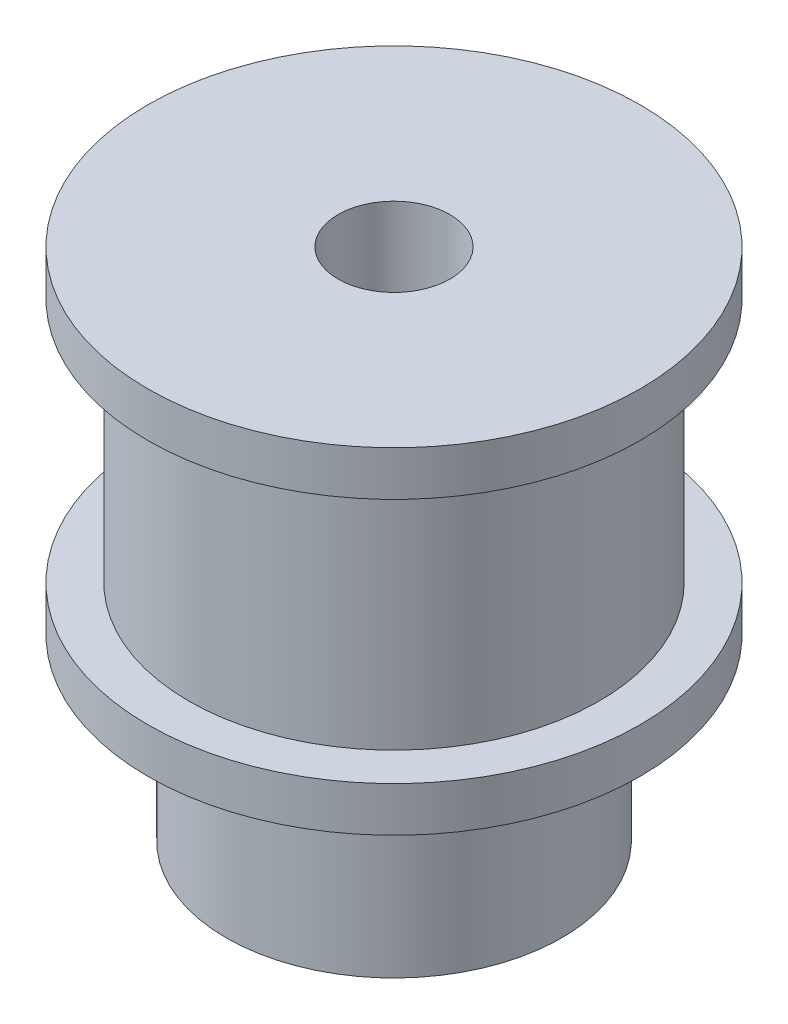
SolidWorks part; units mm, degrees
material "AISI 304"
ref_plane "前视基准面" through (0, 0, 0) normal (0, 0, 1) x (1, 0, 0)
ref_plane "上视基准面" through (0, 0, 0) normal (0, 1, 0) x (1, 0, 0)
ref_plane "右视基准面" through (0, 0, 0) normal (1, 0, 0) x (0, 0, -1)
other "Configuration Table"
sketch "草图1" plane through (0, 0, 0) normal (0, 1, 0) x (1, 0, 0)
  circle A0 centre (0, 0) radius 11
  dimension "D1" = 22
extrude "凸台-拉伸1" add sketch "草图1" along normal blind 2
sketch "草图2" plane through (0, 2, 0) normal (0, 1, 0) x (1, 0, 0)
  circle A0 centre (0, 0) radius 9.17
  dimension "D1" = 18.34
extrude "凸台-拉伸2" add sketch "草图2" along normal blind 11
sketch "草图3" plane through (0, 13, 0) normal (0, 1, 0) x (1, 0, 0)
  circle A0 centre (0, 0) radius 11
  dimension "D1" = 22
extrude "凸台-拉伸3" add sketch "草图3" along normal blind 2
sketch "草图4" plane through (0, 15, 0) normal (0, 1, 0) x (1, 0, 0)
  circle A0 centre (0, 0) radius 2.5
  dimension "D1" = 5
extrude "切除-拉伸1" cut sketch "草图4" against normal blind 26
sketch "草图5" plane through (0, 0, 0) normal (0, -1, 0) x (1, 0, 0)
  circle A0 centre (0, 0) radius 7.5
  circle A1 centre (0, 0) radius 2.5
  dimension "D1" = 5
  dimension "D2" = 15
extrude "凸台-拉伸4" add sketch "草图5" along normal blind 8
